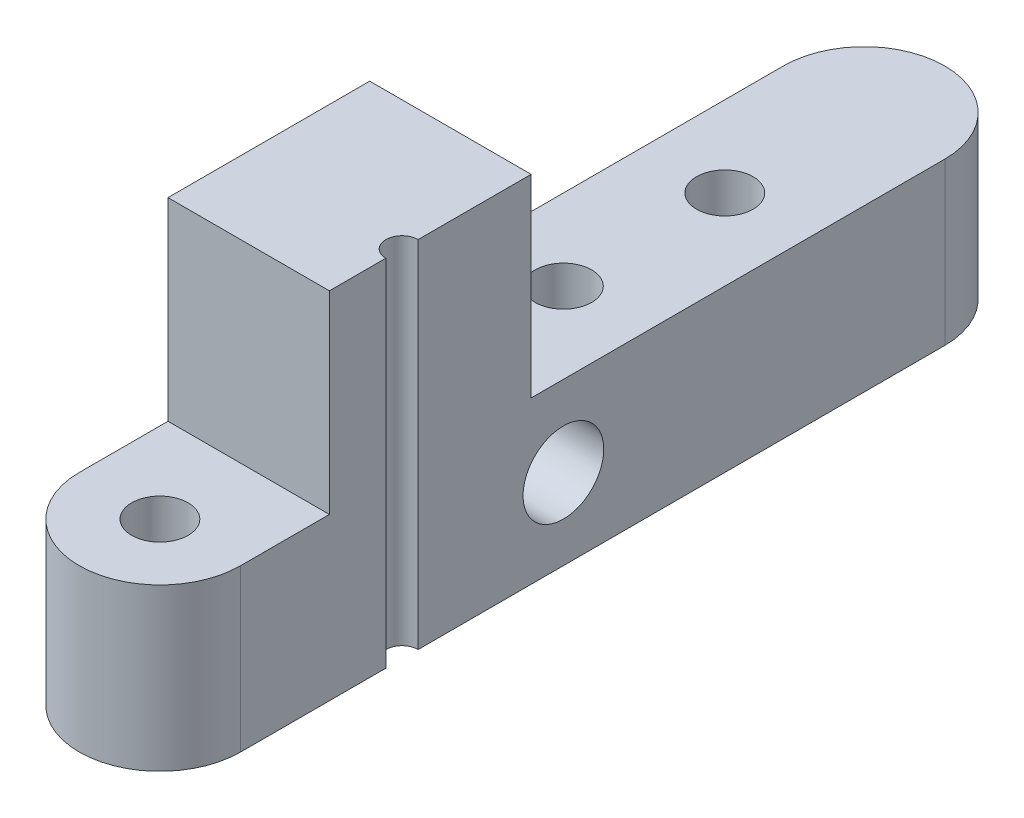
SolidWorks part; units mm, degrees
ref_plane "Front Plane" through (0, 0, 0) normal (0, 0, 1) x (1, 0, 0)
ref_plane "Top Plane" through (0, 0, 0) normal (0, 1, 0) x (1, 0, 0)
ref_plane "Right Plane" through (0, 0, 0) normal (1, 0, 0) x (0, 0, -1)
sketch "Sketch1" plane through (0, 0, 0) normal (0, 1, 0) x (1, 0, 0)
  line L0 (0, 0) -> (0, 43.6303) construction
  line L1 (-5, 0) -> (-5, 43.6303)
  line L2 (5, 0) -> (5, 9)
  line L3 (5, 11) -> (5, 43.6303)
  line L4 (-5, 20) -> (5, 20) construction
  arc A0 (-5, 0) -> (5, 0) centre (0, 0) ccw
  arc A1 (5, 43.6303) -> (-5, 43.6303) centre (0, 43.6303) ccw
  circle A2 centre (0, 0) radius 1.75
  arc A3 (5, 11) -> (5, 9) centre (5, 10) ccw
  circle A4 centre (5, 10) radius 39 construction
  circle A5 centre (0, 15) radius 1.75 construction
  circle A6 centre (0, 25) radius 1.75
  circle A7 centre (0, 35) radius 1.75
  dimension "D1" = 3.5
  dimension "D2" = 2
  dimension "D4" = 5
  dimension "D6" = 78
  dimension "D8" = 3.5
  dimension "D10" = 3
  dimension "D3" = 0
  dimension "D5" = 10
  dimension "D7" = 10
  dimension "D9" = 5
  dimension "D11" = 10
extrude "Boss-Extrude1" add sketch "Sketch1" along normal blind 10
sketch "Sketch2" plane through (5, 0, 0) normal (1, 0, 0) x (0, 0, -1)
  line L0 (10, 0) -> (10, 10) construction
  line L1 (10, 5) -> (20, 5)
  line L4 (9, 0) -> (11, 0)
  line L5 (11, 0) -> (11, 10)
  line L6 (11, 10) -> (9, 10)
  line L7 (9, 10) -> (9, 0)
  line L8 (9, 0) -> (11, 0) construction
  line L9 (11, 0) -> (11, 10) construction
  line L10 (11, 10) -> (9, 10) construction
  line L11 (9, 10) -> (9, 0) construction
  circle A0 centre (20, 5) radius 2.5
  dimension "D2" = 5
  dimension "D3" = 10
  dimension "D1" = 0
extrude "Cut-Extrude1" cut sketch "Sketch2" against normal through all
sketch "Sketch3" plane through (0, 10, 0) normal (0, 1, 0) x (1, 0, 0)
  line L1 (5, 5.5) -> (-5, 5.5)
  line L2 (5, 5.5) -> (5, 9)
  line L3 (5, 18) -> (-5, 18)
  line L4 (-5, 5.5) -> (-5, 18)
  line L5 (5, 11) -> (5, 18)
  line L6 (-5, 43.6303) -> (-5, 0) construction
  line L7 (5, 11) -> (5, 43.6303) construction
  circle A0 centre (0, 0) radius 5.5 construction
  arc A1 (5, 11) -> (5, 9) centre (5, 10) ccw construction
  arc A2 (5, 11) -> (5, 9) centre (5, 10) ccw
  dimension "D1" = 11
  dimension "D2" = 12.5
extrude "Boss-Extrude2" add sketch "Sketch3" along normal blind 12
ref_plane "Plane1" through (0, 0, -55) normal (0, 0, 1) x (1, 0, 0)
sketch "Sketch4" plane through (0, 0, -55) normal (0, 0, 1) x (1, 0, 0)
  line L0 (0, 0) -> (0, 5) construction
  line L1 (0, 5) -> (-5, 5) construction
  line L2 (-5, 10) -> (-5, 0) construction
  line L3 (-5, 5) -> (0, 5)
  circle A0 centre (0, 5) radius 2
  dimension "D1" = 4
extrude "Cut-Extrude2" cut sketch "Sketch4" along normal blind 25 contours A0
